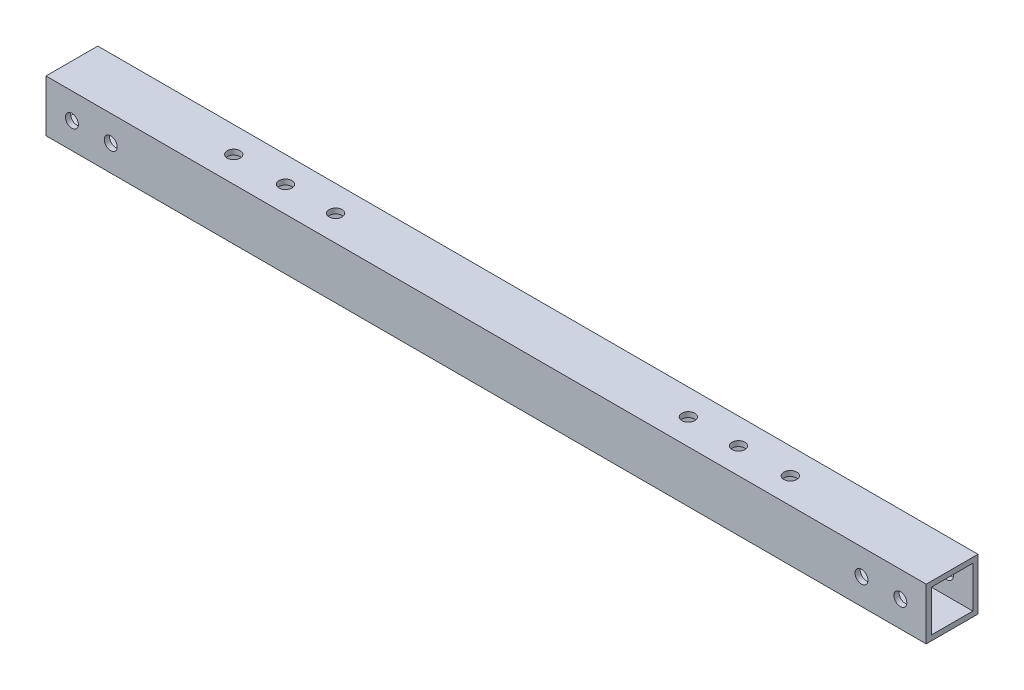
SolidWorks part; units mm, degrees
material "1345 Alloy"
ref_plane "Front Plane" through (0, 0, 0) normal (0, 0, 1) x (1, 0, 0)
ref_plane "Top Plane" through (0, 0, 0) normal (0, 1, 0) x (1, 0, 0)
ref_plane "Right Plane" through (0, 0, 0) normal (1, 0, 0) x (0, 0, -1)
sketch "Sketch1" plane through (0, 0, 0) normal (1, 0, 0) x (0, 0, -1)
  line L1 (-10, 10) -> (10, 10)
  line L2 (-10, 10) -> (-10, -10)
  line L3 (-10, -10) -> (10, -10)
  line L4 (10, 10) -> (10, -10)
  line L5 (-10, 10) -> (10, -10) construction
  line L6 (-10, -10) -> (10, 10) construction
  line L7 (-8, 8) -> (8, 8)
  line L8 (-8, 8) -> (-8, -8)
  line L9 (-8, -8) -> (8, -8)
  line L10 (8, 8) -> (8, -8)
  line L11 (-8, 8) -> (8, -8) construction
  line L12 (-8, -8) -> (8, 8) construction
  point P0 (0, 0)
  point P6 (0, 0)
  dimension "D1" = 20
  dimension "D2" = 20
  dimension "D3" = 16
extrude "Boss-Extrude1" add sketch "Sketch1" along normal blind 340
sketch "Sketch2" plane through (0, 0, 10) normal (0, 0, 1) x (1, 0, 0)
  line L0 (170, 10) -> (170, -10) construction
  line L1 (340, 10) -> (0, 10) construction
  line L2 (340, -10) -> (0, -10) construction
  line L3 (-6.6959, 0) -> (348.2418, 0) construction
  circle A0 centre (10, 0) radius 2.5
  circle A1 centre (25, 0) radius 2.5
  circle A4 centre (315, 0) radius 2.5
  circle A5 centre (330, 0) radius 2.5
  dimension "D1" = 5
  dimension "D2" = 5
  dimension "D3" = 15
  dimension "D5" = 160
extrude "Cut-Extrude1" cut sketch "Sketch2" against normal through all
sketch "Sketch3" plane through (0, 10, 0) normal (0, 1, 0) x (1, 0, 0)
  line L0 (170, 10) -> (170, -36.7055) construction
  line L1 (340, 10) -> (0, 10) construction
  line L2 (0, 25.3752) -> (0, -39.066) construction
  line L3 (72.5, 25.3752) -> (72.5, -39.066) construction
  line L4 (-10.8132, 0) -> (177.3175, 0) construction
  circle A0 centre (62.5, 0) radius 2.5
  circle A1 centre (82.5, 0) radius 2.5
  circle A2 centre (257.5, 0) radius 2.5
  circle A3 centre (277.5, 0) radius 2.5
  dimension "D2" = 5
  dimension "D3" = 10
  dimension "D1" = 72.5
extrude "Cut-Extrude2" cut sketch "Sketch3" against normal through all
sketch "Sketch4" plane through (0, 10, 0) normal (0, 1, 0) x (1, 0, 0)
  line L0 (-9.6329, 0) -> (358.6028, 0) construction
  line L1 (170, 10) -> (170, -10) construction
  line L2 (340, 10) -> (0, 10) construction
  line L3 (340, -10) -> (0, -10) construction
  circle A0 centre (101.88, 0) radius 2.5
  circle A1 centre (82.5, 0) radius 2.5 construction
  circle A2 centre (238.12, 0) radius 2.5
  dimension "D1" = 5
  dimension "D2" = 19.38
extrude "Cut-Extrude3" cut sketch "Sketch4" against normal through all
